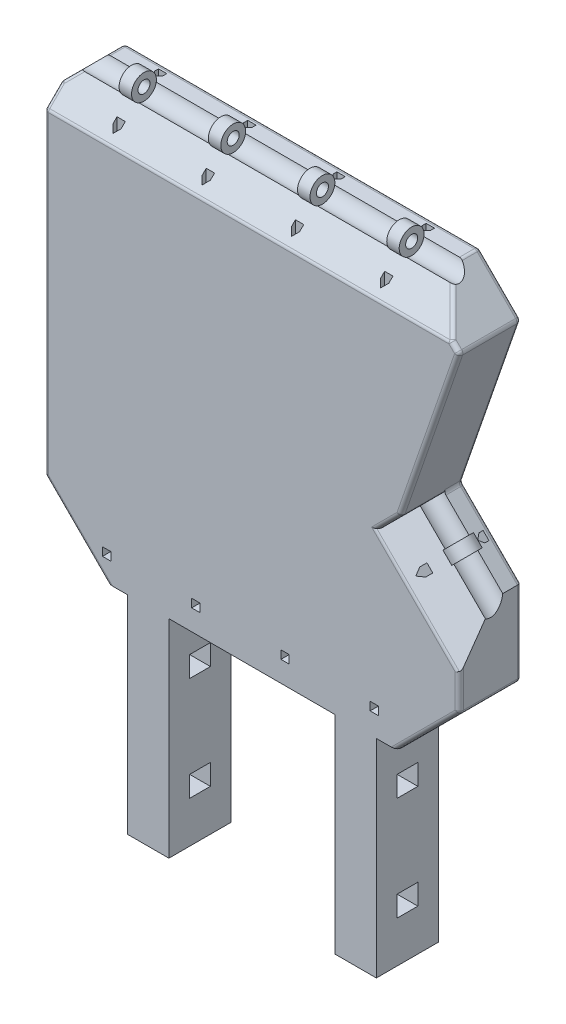
SolidWorks part; units mm, degrees
material "Custom Plastic"
ref_plane "Front Plane" through (0, 0, 0) normal (0, 0, 1) x (1, 0, 0)
ref_plane "Top Plane" through (0, 0, 0) normal (0, 1, 0) x (1, 0, 0)
ref_plane "Right Plane" through (0, 0, 0) normal (1, 0, 0) x (0, 0, -1)
sketch "Sketch1" plane through (0, 0, 0) normal (0, 0, 1) x (1, 0, 0)
  line L1 (-50, -50) -> (50, -50)
  line L2 (-50, -50) -> (-50, 50)
  line L3 (-50, 50) -> (50, 50)
  line L4 (50, -50) -> (50, 50)
  line L5 (-50, -50) -> (50, 50) construction
  line L6 (-50, 50) -> (50, -50) construction
  point P0 (0, 0)
  dimension "D1" = 100
  dimension "D2" = 100
extrude "Boss-Extrude1" add sketch "Sketch1" along normal mid plane 15
sketch "Sketch2" plane through (0, 0, 0) normal (0, 0, 1) x (1, 0, 0)
  line L0 (-50, 45) -> (-45, 50)
  line L1 (-50, 50) -> (-50, -50) construction
  line L2 (50, 50) -> (-50, 50) construction
  line L3 (-45, 50) -> (40, 50)
  line L4 (40, 50) -> (50, 40)
  line L5 (50, -50) -> (50, 50) construction
  line L6 (50, 40) -> (35.8579, -0.8579)
  line L7 (35.8579, -0.8579) -> (50, -15)
  line L8 (50, -15) -> (50, -35)
  line L9 (50, -35) -> (35, -50)
  line L10 (-50, -50) -> (50, -50) construction
  line L11 (35, -50) -> (-35, -50)
  line L12 (-35, -50) -> (-50, -35)
  line L13 (-50, -35) -> (-50, 45)
  dimension "D1" = 5
  dimension "D2" = 10
  dimension "D3" = 5
  dimension "D4" = 10
  dimension "D5" = 20
  dimension "D6" = 15
  dimension "D7" = 15
  dimension "D8" = 20
  dimension "D9" = 135
extrude "Cut-Extrude6" cut sketch "Sketch2" against normal through all both and the other way through all flip side to cut
ref_plane "Plane1" through (29.5, 0, 0) normal (1, 0, 0) x (0, 0, -1)
sketch "Sketch9" plane through (0, 0, 0) normal (1, 0, 0) x (0, 0, -1)
  line L0 (-7.5, 50) -> (0, 50)
  line L1 (7.5, 50) -> (-7.5, 50) construction
  line L2 (0, 50) -> (0, 49)
  line L3 (0, 49) -> (-7.5, 41.5)
  line L4 (-7.5, 40) -> (-7.5, 50) construction
  line L5 (-7.5, 41.5) -> (-7.5, 50)
  dimension "D1" = 1
  dimension "D2" = 7.5
  dimension "D3" = 45
extrude "Cut-Extrude7" cut sketch "Sketch9" against normal through all both and the other way through all
sketch "Sketch10" plane through (29.5, 0, 0) normal (1, 0, 0) x (0, 0, -1)
  line L0 (7.5, 50) -> (0, 50) construction
  line L3 (0, 49) -> (0, 50) construction
  circle A0 centre (0, 50.5) radius 3
  dimension "D1" = 6
  dimension "D2" = 0.5
  dimension "D3" = 0
extrude "Boss-Extrude3" add sketch "Sketch10" along normal mid plane 3
sketch "Sketch11" plane through (31, 0, 0) normal (1, 0, 0) x (0, 0, -1)
  circle A0 centre (0, 50.5) radius 3
extrude "Cut-Extrude8" cut sketch "Sketch11" along normal blind 12
mirror "Mirror2" about plane through (29.5, 0, 0) normal (1, 0, 0) of "Cut-Extrude8"
sketch "Sketch12" plane through (29.5, 0, 0) normal (1, 0, 0) x (0, 0, -1)
  circle A0 centre (0, 50.5) radius 1
  dimension "D1" = 2
pattern_linear "LPattern1" count 4 spacing 21.5 along (-1, 0, 0) of "Boss-Extrude3"
pattern_linear "LPattern2" count 4 spacing 21.5 along (-1, 0, 0) of "Mirror2", "Cut-Extrude8"
sketch "Sketch13" plane through (29.5, 0, 0) normal (1, 0, 0) x (0, 0, -1)
  circle A0 centre (0, 50.5) radius 1.45
  dimension "D1" = 2.9
extrude "Cut-Extrude10" cut sketch "Sketch13" against normal through all both and the other way through all
ref_plane "Plane2" through (32.5, -32.5, 0) normal (-0.7071, 0.7071, 0) x (0, 0, 1)
sketch "Sketch14" plane through (32.5, -32.5, 0) normal (-0.7071, 0.7071, 0) x (0, 0, 1)
  line L0 (7.5, 24.7487) -> (0, 24.7487)
  line L1 (-7.5, 24.7487) -> (7.5, 24.7487) construction
  line L2 (0, 24.7487) -> (0, 23.7487)
  line L3 (0, 23.7487) -> (7.5, 16.2487)
  line L4 (7.5, 16.2487) -> (7.5, 24.7487)
  dimension "D1" = 1
  dimension "D2" = 45
  dimension "D3" = 0
  dimension "D4" = 7.5
extrude "Cut-Extrude12" cut sketch "Sketch14" against normal blind 20 and the other way blind 20
ref_plane "Plane3" through (25.4289, -25.4289, 0) normal (-0.7071, 0.7071, 0) x (0, 0, 1)
sketch "Sketch16" plane through (25.4289, -25.4289, 0) normal (-0.7071, 0.7071, 0) x (0, 0, 1)
  circle A0 centre (0, 25.2487) radius 3
  dimension "D1" = 6
  dimension "D2" = 0.5
extrude "Boss-Extrude4" add sketch "Sketch16" along normal mid plane 3
sketch "Sketch17" plane through (26.4896, -26.4896, 0) normal (0.7071, -0.7071, 0) x (0, 0, -1)
  circle A0 centre (0, 25.2487) radius 3
extrude "Cut-Extrude13" cut sketch "Sketch17" along normal blind 8.5
mirror "Mirror3" about plane through (25.4289, -25.4289, 0) normal (-0.7071, 0.7071, 0) of "Cut-Extrude13"
sketch "Sketch18" plane through (32.5, -32.5, 0) normal (-0.7071, 0.7071, 0) x (0, 0, 1)
  circle A0 centre (0, 25.2487) radius 1.45
  dimension "D1" = 2.9
extrude "Cut-Extrude14" cut sketch "Sketch18" along normal blind 14.14
sketch "Sketch19" plane through (0, 0, 0) normal (0, 1, 0) x (1, 0, 0)
  line L0 (28.5, -4) -> (30.5, -4)
  line L1 (30.5, -4) -> (30.5, -5)
  line L2 (30.5, -5) -> (29.5, -6)
  line L3 (29.5, -6) -> (28.5, -5)
  line L4 (28.5, -5) -> (28.5, -4)
  line L5 (29.5, -8.25) -> (29.5, 8.25) construction
  line L6 (28, -3) -> (31, -3) construction
  dimension "D1" = 1
  dimension "D2" = 1
  dimension "D3" = 1
  dimension "D4" = 135
  dimension "D5" = 135
  dimension "D6" = 1
  dimension "D7" = 1
extrude "Cut-Extrude16" cut sketch "Sketch19" along normal through all and the other way blind 45
ref_plane "Plane4" through (0, 0, 4) normal (0, 0, 1) x (1, 0, 0)
sketch "Sketch20" plane through (0, 0, 4) normal (0, 0, 1) x (1, 0, 0)
  line L0 (29.5, -8.25) -> (29.5, 8.25) construction
  line L1 (28.5, -45) -> (30.5, -45)
  line L2 (28.5, -45) -> (28.5, -43)
  line L3 (28.5, -43) -> (30.5, -43)
  line L4 (30.5, -45) -> (30.5, -43)
  line L5 (28.5, -45) -> (30.5, -43) construction
  line L6 (28.5, -43) -> (30.5, -45) construction
  line L7 (-35, -50) -> (35, -50) construction
  point P0 (29.5, -44)
  dimension "D1" = 2
  dimension "D2" = 2
  dimension "D3" = 5
extrude "Cut-Extrude17" cut sketch "Sketch20" along normal through all
pattern_linear "LPattern3" count 4 spacing 21.5 along (-1, 0, 0) of "Cut-Extrude16"
pattern_linear "LPattern4" count 4 spacing 21.5 along (-1, 0, 0) of "Cut-Extrude17", "Cut-Extrude16"
sketch "Sketch21" plane through (17.5, 17.5, 0) normal (0.7071, 0.7071, 0) x (0, 0, -1)
  line L0 (-4, -34.9619) -> (-4, -36.9619)
  line L1 (-4, -36.9619) -> (-5, -36.9619)
  line L2 (-5, -36.9619) -> (-6, -35.9619)
  line L3 (-6, -35.9619) -> (-5, -34.9619)
  line L4 (-5, -34.9619) -> (-4, -34.9619)
  line L7 (3.575, -35.9619) -> (-3.575, -35.9619) construction
  line L8 (-3, -34.4619) -> (-3, -37.4619) construction
  dimension "D1" = 2
  dimension "D2" = 1
  dimension "D3" = 1
  dimension "D4" = 135
  dimension "D5" = 1
  dimension "D6" = 1
extrude "Cut-Extrude18" cut sketch "Sketch21" against normal up to surface (19.4056 mm away)
sketch "Sketch22" plane through (0, 0, 0) normal (0, 1, 0) x (1, 0, 0)
  line L0 (28.5, 6) -> (30.5, 6)
  line L1 (30.5, 6) -> (30.5, 5)
  line L2 (30.5, 5) -> (29.5, 4)
  line L3 (29.5, 4) -> (28.5, 5)
  line L4 (28.5, 5) -> (28.5, 6)
  line L5 (29.5, -8.25) -> (29.5, 8.25) construction
  line L6 (31, 3) -> (28, 3) construction
  dimension "D1" = 1
  dimension "D2" = 2
  dimension "D3" = 1
  dimension "D4" = 135
  dimension "D5" = 135
  dimension "D6" = 1
  dimension "D7" = 1
extrude "Cut-Extrude19" cut sketch "Sketch22" along normal through all and the other way blind 45
ref_plane "Plane5" through (0, 0, -6) normal (0, 0, 1) x (1, 0, 0)
sketch "Sketch23" plane through (0, 0, -6) normal (0, 0, 1) x (1, 0, 0)
  line L0 (29.5, -8.25) -> (29.5, 8.25) construction
  line L1 (30.5, -45) -> (28.5, -45)
  line L2 (30.5, -45) -> (30.5, -43)
  line L3 (30.5, -43) -> (28.5, -43)
  line L4 (28.5, -45) -> (28.5, -43)
  line L5 (30.5, -45) -> (28.5, -43) construction
  line L6 (30.5, -43) -> (28.5, -45) construction
  line L7 (-35, -50) -> (35, -50) construction
  point P0 (29.5, -44)
  dimension "D1" = 2
  dimension "D2" = 2
  dimension "D3" = 1
  dimension "D4" = 5
extrude "Cut-Extrude20" cut sketch "Sketch23" against normal through all
pattern_linear "LPattern5" count 4 spacing 21.5 along (-1, 0, 0) of "Cut-Extrude19", "Cut-Extrude20"
sketch "Sketch24" plane through (17.5, 17.5, 0) normal (0.7071, 0.7071, 0) x (0, 0, -1)
  line L1 (6, -34.9619) -> (6, -36.9619)
  line L2 (6, -36.9619) -> (5, -36.9619)
  line L3 (5, -36.9619) -> (4, -35.9619)
  line L4 (4, -35.9619) -> (5, -34.9619)
  line L5 (5, -34.9619) -> (6, -34.9619)
  line L6 (3.575, -35.9619) -> (-3.575, -35.9619) construction
  line L7 (3, -37.4619) -> (3, -34.4619) construction
  dimension "D1" = 2
  dimension "D2" = 1
  dimension "D3" = 90
  dimension "D4" = 1
  dimension "D5" = 135
  dimension "D6" = 135
  dimension "D7" = 1
  dimension "D8" = 1
extrude "Cut-Extrude21" cut sketch "Sketch24" against normal up to surface (21.4056 mm away)
fillet "Fillet6" radius 1 1 edges at (35.8579, -0.8579, -5.229)
fillet "Fillet7" radius 1 31 edges at (36.0331, -0.8176, -7.5) (50, 40, 0) (45.3672, 44.6328, 4.3672) (-48.6172, 46.3828, 2.6172) (35.8579, -0.8579, 2.271) (50, -25, -7.5) (-45, 50, -5.229) (-2.5, 50, -7.5) (35, -50, 0) (-50, 43.25, 5.75) (-50, -35, 0) (-50, 45, -1.75) (-50, 5, -7.5) (-35, -50, 0) (-42.5, -42.5, -7.5) (50, -35, 0) (42.5, -42.5, -7.5) (43.0313, 19.8668, -7.5) (40, 50, -5.229) (45, 45, -7.5) (43.1503, -8.1503, -7.5) (50, -31.0104, 7.5) (-50, 3.25, 7.5) (-0.75, 41.5, 7.5) (-42.5, -42.5, 7.5) (42.5, -42.5, 7.5) (42.9289, 19.5711, 7.5) (49.25, 40.75, 7.5) (39.9237, -16.9445, 7.5) (32.8527, -3.8631, 7.5) (-47.5, 47.5, -7.5)
sketch "Sketch25" plane through (0, -50, 0) normal (0, -1, 0) x (1, 0, 0)
  line L0 (-33.5858, 7.5) -> (33.5858, 7.5) construction
  line L1 (-30, -7.5) -> (-20, -7.5)
  line L2 (-30, -7.5) -> (-30, 7.5)
  line L3 (-30, 7.5) -> (-20, 7.5)
  line L4 (-20, -7.5) -> (-20, 7.5)
  line L5 (-30, -7.5) -> (-20, 7.5) construction
  line L6 (-30, 7.5) -> (-20, -7.5) construction
  line L8 (0, -8.25) -> (0, 8.25) construction
  line L9 (30, 7.5) -> (20, 7.5)
  line L10 (20, -7.5) -> (20, 7.5)
  line L11 (30, -7.5) -> (20, -7.5)
  line L12 (30, -7.5) -> (30, 7.5)
  point P0 (-25, 0)
  dimension "D1" = 15
  dimension "D2" = 10
  dimension "D3" = 20
extrude "Boss-Extrude5" add sketch "Sketch25" along normal blind 50
sketch "Sketch26" plane through (-20, 0, 0) normal (1, 0, 0) x (0, 0, -1)
  line L0 (7.5, -100) -> (-7.5, -100) construction
  line L1 (-2.5, -85) -> (2.5, -85)
  line L2 (-2.5, -85) -> (-2.5, -90)
  line L3 (-2.5, -90) -> (2.5, -90)
  line L4 (2.5, -85) -> (2.5, -90)
  line L5 (-2.5, -85) -> (2.5, -90) construction
  line L6 (-2.5, -90) -> (2.5, -85) construction
  line L7 (-2.5, -60) -> (2.5, -60)
  line L8 (-2.5, -60) -> (-2.5, -65)
  line L9 (-2.5, -65) -> (2.5, -65)
  line L10 (2.5, -60) -> (2.5, -65)
  line L11 (-2.5, -60) -> (2.5, -65) construction
  line L12 (-2.5, -65) -> (2.5, -60) construction
  point P0 (0, -87.5)
  point P5 (0, -62.5)
  point P12 (0, -100)
  point P14 (0, -85)
  dimension "D1" = 5
  dimension "D2" = 5
  dimension "D3" = 5
  dimension "D4" = 5
  dimension "D5" = 10
  dimension "D6" = 20
extrude "Cut-Extrude22" cut sketch "Sketch26" against normal through all both and the other way through all
sketch "Sketch27" plane through (26.4896, -26.4896, 0) normal (0.7071, -0.7071, 0) x (0, 0, -1)
  circle A0 centre (0, 25.2487) radius 3
extrude "Cut-Extrude23" cut sketch "Sketch27" along normal through all
